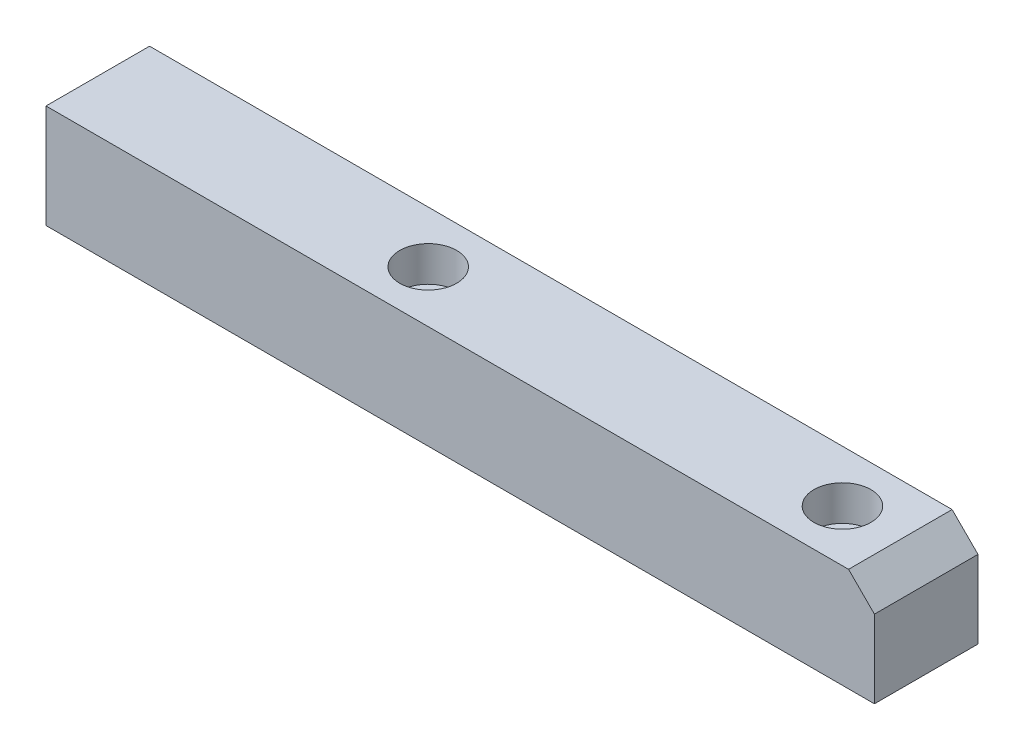
SolidWorks part; units mm, degrees
material "6061 Alloy"
ref_plane "Front Plane" through (0, 0, 0) normal (0, 0, 1) x (1, 0, 0)
ref_plane "Top Plane" through (0, 0, 0) normal (0, 1, 0) x (1, 0, 0)
ref_plane "Right Plane" through (0, 0, 0) normal (1, 0, 0) x (0, 0, -1)
sketch "Sketch1" plane through (0, 0, 0) normal (0, 1, 0) x (1, 0, 0)
  line L1 (80, -10) -> (-80, -10)
  line L2 (80, -10) -> (80, 10)
  line L3 (80, 10) -> (-80, 10)
  line L4 (-80, -10) -> (-80, 10)
  line L5 (80, -10) -> (-80, 10) construction
  line L6 (80, 10) -> (-80, -10) construction
  point P0 (0, 0)
  dimension "D1" = 160
  dimension "D2" = 20
extrude "Boss-Extrude1" add sketch "Sketch1" along normal mid plane 20
hole_wizard "CBORE for M6 Slotted cheese head screws2" positions "Sketch2" profile "Sketch3" counterbore size "M6" standard "GB" end condition through all
sketch "Sketch2" plane through (0, 10, 0) normal (0, 1, 0) x (1, 0, 0)
  line L0 (-80, 10) -> (-80, -10) construction
  point P0 (-16.182, 0)
  point P2 (63.818, 0)
  point P7 (0, 0)
  point P8 (0, 0)
  dimension "D1" = 63.818
  dimension "D2" = 80
sketch "Sketch3" plane through (-16.182, 10, 0) normal (1, 0, 0) x (0, 0, 1)
  line L0 (0, 0) -> (0, 20)
  line L1 (0, 20) -> (3.3, 20)
  line L3 (3.3, 20) -> (3.3, 6.8)
  line L4 (3.3, 6.8) -> (5.5, 6.8)
  line L5 (5.5, 6.8) -> (5.5, 0)
  line L7 (5.5, 0) -> (0, 0)
  line L11 (0, -6.35) -> (0, 107.95) construction
  dimension "Thru Hole Dia." = 6.6
  dimension "Thru Hole Depth" = 20
  dimension "C'Bore Dia." = 11
  dimension "C'Bore Depth" = 6.8
hole_wizard "M6 Tapped Hole1" positions "Sketch5" profile "Sketch6" tap size "M6" standard "GB"
sketch "Sketch5" plane through (-80, 0, 0) normal (-1, 0, 0) x (0, 0, 1)
  point P0 (0, 0)
sketch "Sketch6" plane through (-80, 0, 0) normal (0, 1, 0) x (0, 0, 1)
  line L0 (0, 0) -> (0, 16.5022)
  line L1 (0, 16.5022) -> (2.5, 15)
  line L2 (2.5, 15) -> (2.5, 0)
  line L5 (2.5, 0) -> (0, 0)
  line L10 (0, 16.5022) -> (-2.5, 15) construction
  line L11 (0, -6.35) -> (0, 107.95) construction
  dimension "Tap Drill Dia." = 5
  dimension "Tap Drill Depth" = 15
  dimension "Drill Angle" = 118
chamfer "Chamfer1" distance 5 angle 45 1 edges at (80, 10, 0)
